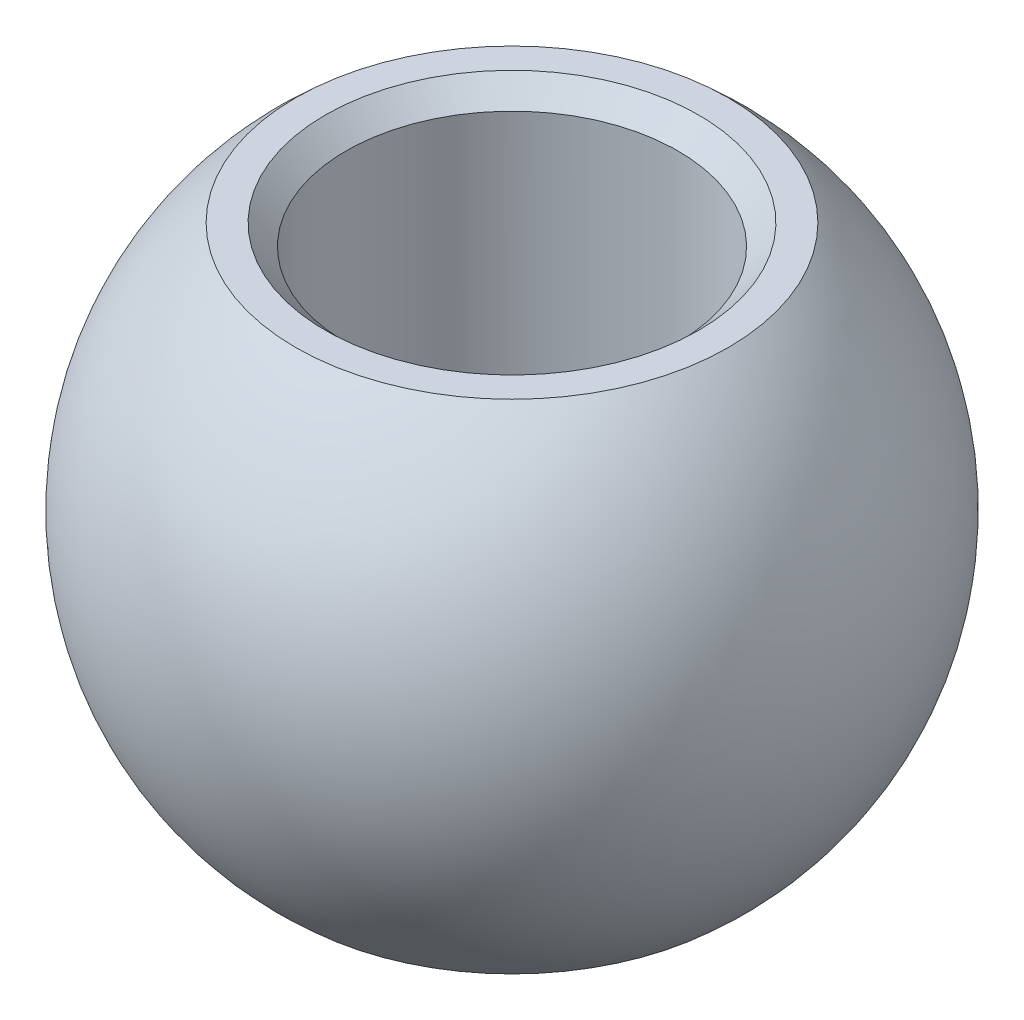
SolidWorks part; units mm, degrees
material "20MnV6"
ref_plane "Front Plane" through (0, 0, 0) normal (0, 0, 1) x (1, 0, 0)
ref_plane "Top Plane" through (0, 0, 0) normal (0, 1, 0) x (1, 0, 0)
ref_plane "Right Plane" through (0, 0, 0) normal (1, 0, 0) x (0, 0, -1)
sketch "Sketch1" plane through (0, 0, 0) normal (0, 0, 1) x (1, 0, 0)
  line L0 (-5.2156, -6) -> (-4, -6)
  line L1 (0, -6) -> (0, 6) construction
  line L2 (-4, -6) -> (-4, 6)
  line L3 (-4, 6) -> (-5.2156, 6)
  line L4 (0, 6) -> (-4, 6) construction
  line L5 (0, -6) -> (-4, -6) construction
  arc A0 (-5.2156, 6) -> (-5.2156, -6) centre (0, 0) ccw
  dimension "D2" = 7.95
  dimension "D1" = 4
  dimension "D3" = 12
revolve "Revolve1" add sketch "Sketch1" angle 360 about L1
chamfer "Chamfer1" distance 0.5 angle 45 2 edges at (4, -6, 0) (4, 6, 0)
